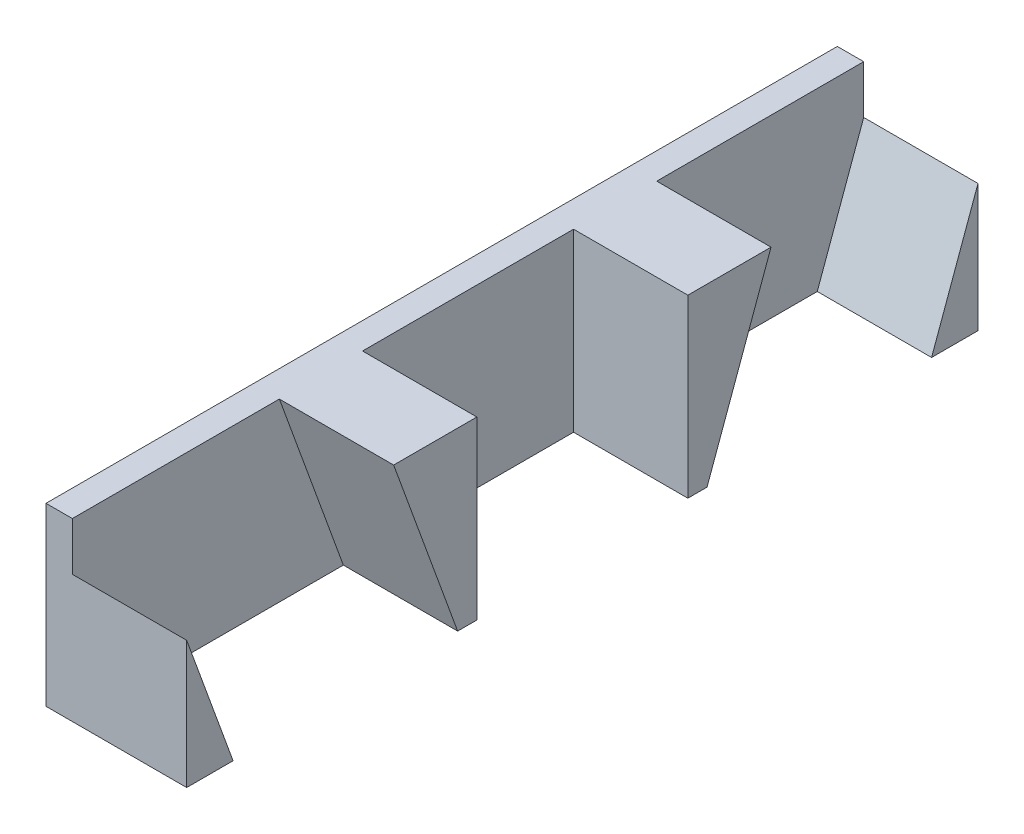
SolidWorks part; units mm, degrees
material "ABS"
ref_plane "Front Plane" through (0, 0, 0) normal (0, 0, 1) x (1, 0, 0)
ref_plane "Top Plane" through (0, 0, 0) normal (0, 1, 0) x (1, 0, 0)
ref_plane "Right Plane" through (0, 0, 0) normal (1, 0, 0) x (0, 0, -1)
sketch "Croquis1" plane through (0, 0, 0) normal (0, 0, 1) x (1, 0, 0)
  line L0 (-3.5, 49.5) -> (-3.5, 0)
  line L1 (-3.5, 0) -> (0, 0)
  line L2 (0, 0) -> (0, 41.9942)
  line L3 (0, 41.9942) -> (-3.5, 49.5)
  dimension "D1" = 3.5
  dimension "D2" = 49.5
  dimension "D3" = 25
extrude "Saliente-Extruir1" add sketch "Croquis1" along normal blind 49
sketch "Croquis2" plane through (0, 0, 0) normal (1, 0, 0) x (0, 0, -1)
  line L0 (-49, 0) -> (0, 0)
  line L2 (-49, 0) -> (-49, 28.9942)
  line L3 (-49, 28.9942) -> (-34.5, 28.9942)
  line L4 (-34.5, 4.5) -> (-34.5, 28.9942)
  line L6 (0, 0) -> (0, 28.9942)
  line L7 (0, 28.9942) -> (-14.5, 28.9942)
  line L8 (-14.5, 4.5) -> (-14.5, 28.9942)
  line L11 (-34.5, 4.5) -> (-14.5, 4.5)
  line L12 (-49, 41.9942) -> (0, 41.9942) construction
  point P14 (-24.5, 35.4942)
  dimension "D1" = 13
  dimension "D2" = 20
  dimension "D3" = 4.5
  dimension "D4" = 13
extrude "Cortar-Extruir1" cut sketch "Croquis2" against normal through all
sketch "Croquis4" plane through (0, 28.9942, 0) normal (0, -1, 0) x (1, 0, 0)
  line L0 (0, 49) -> (20.5, 49)
  line L2 (20.5, 0) -> (0, 0)
  line L6 (12.5, 47.5) -> (12.5, 1.5)
  line L8 (12.5, 47.5) -> (0, 47.5)
  line L9 (0, 34.5) -> (0, 49) construction
  line L10 (0, 47.5) -> (0, 49)
  line L11 (12.5, 1.5) -> (0, 1.5)
  line L12 (0, 0) -> (0, 14.5) construction
  line L13 (0, 1.5) -> (0, 0)
  line L22 (20.5, 49) -> (20.5, 0)
  dimension "D1" = 46
  dimension "D2" = 8
  dimension "D3" = 12.5
extrude "Saliente-Extruir3" add sketch "Croquis4" against normal blind 10
sketch "Croquis8" plane through (20.5, 0, 0) normal (1, 0, 0) x (0, 0, -1)
  line L0 (-30.5, 38.9942) -> (-18.5, 38.9942)
  line L1 (0, 38.9942) -> (-49, 38.9942) construction
  line L2 (0, 28.9942) -> (-49, 28.9942) construction
  line L4 (-18.5, 28.9942) -> (-18.5, 38.9942)
  line L10 (-30.5, 28.9942) -> (-30.5, 38.9942)
  line L11 (-30.5, 28.9942) -> (-18.5, 28.9942)
  line L12 (-48, 38.9942) -> (-44.3603, 28.9942)
  line L13 (-49, 38.9942) -> (-49, 28.9942) construction
  line L15 (-35.2299, 38.9942) -> (-31.5902, 28.9942)
  line L16 (-31.5902, 28.9942) -> (-44.3603, 28.9942)
  line L17 (-48, 38.9942) -> (-35.2299, 38.9942)
  line L18 (-17.4098, 28.9942) -> (-4.6397, 28.9942)
  line L19 (-1, 38.9942) -> (-4.6397, 28.9942)
  line L20 (-13.7701, 38.9942) -> (-17.4098, 28.9942)
  line L21 (-1, 38.9942) -> (-13.7701, 38.9942)
  dimension "D1" = 20
  dimension "D2" = 1
extrude "Cortar-Extruir2" cut sketch "Croquis8" against normal blind 6.5
sketch "Croquis9" plane through (0, 0, 0) normal (1, 0, 0) x (0, 0, -1)
  line L0 (-14.5, 28.9942) -> (-14.5, 4.5) construction
  line L1 (-34.5, 4.5) -> (-14.5, 4.5)
  line L2 (-34.5, 4.5) -> (-34.5, 16.5)
  line L3 (-34.5, 16.5) -> (-14.5, 16.5)
  line L4 (-14.5, 4.5) -> (-14.5, 16.5)
  dimension "D1" = 12
extrude "Saliente-Extruir4" add sketch "Croquis9" along normal blind 1.5
sketch "Croquis10" plane through (-3.5, 0, 0) normal (-1, 0, 0) x (0, 0, 1)
  line L1 (0, 49.5) -> (49, 49.5)
  line L2 (0, 49.5) -> (0, 4.5)
  line L3 (0, 4.5) -> (49, 4.5)
  line L4 (49, 49.5) -> (49, 4.5)
extrude "Cortar-Extruir6" cut sketch "Croquis10" against normal blind 16
sketch "Croquis13" plane through (20.5, 0, 0) normal (1, 0, 0) x (0, 0, -1)
  line L0 (0, 28.9942) -> (-4.6397, 28.9942) construction
  line L1 (-49, 38.9942) -> (-47, 38.9942)
  line L2 (-49, 38.9942) -> (-49, 28.9942)
  line L3 (-49, 28.9942) -> (-47, 28.9942)
  line L4 (-47, 38.9942) -> (-47, 28.9942)
  line L5 (0, 38.9942) -> (-2, 38.9942)
  line L6 (0, 38.9942) -> (0, 28.9942)
  line L7 (0, 28.9942) -> (-2, 28.9942)
  line L8 (-2, 38.9942) -> (-2, 28.9942)
extrude "Cortar-Extruir7" cut sketch "Croquis13" against normal through all
